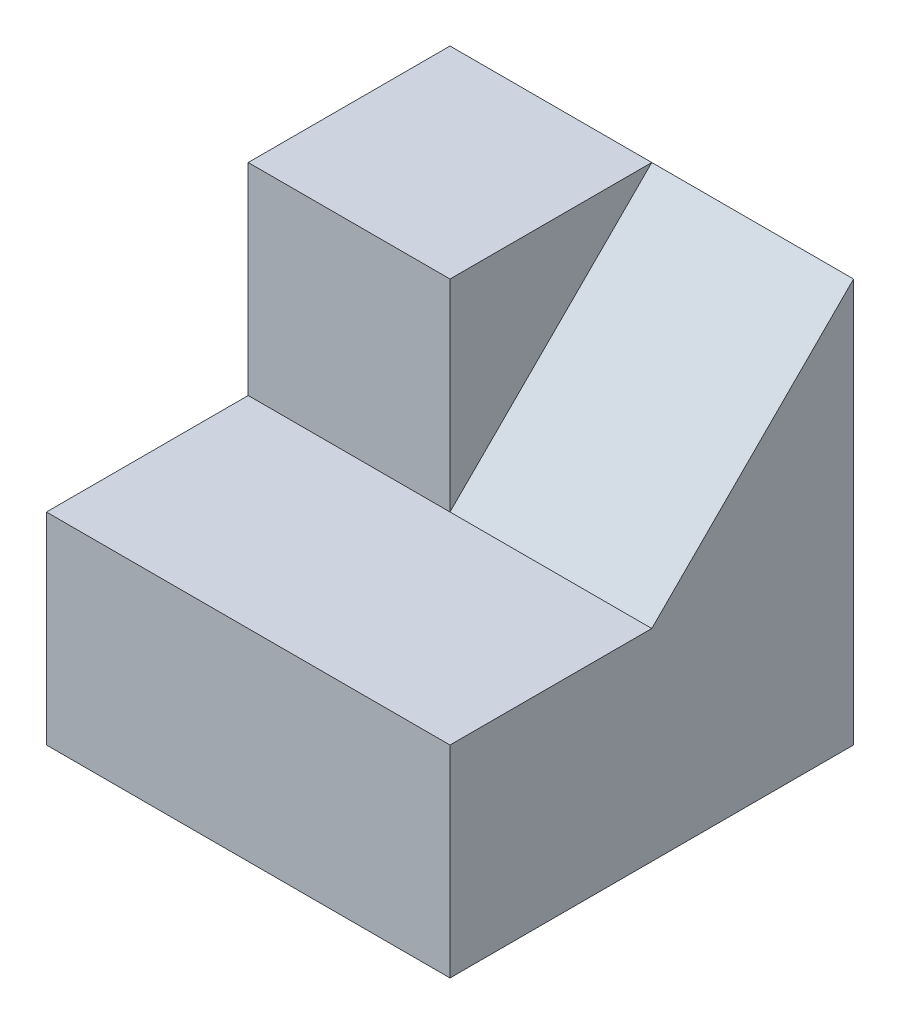
SolidWorks part; units mm, degrees
ref_plane "Alzado" through (0, 0, 0) normal (0, 0, 1) x (1, 0, 0)
ref_plane "Planta" through (0, 0, 0) normal (0, 1, 0) x (1, 0, 0)
ref_plane "Vista lateral" through (0, 0, 0) normal (1, 0, 0) x (0, 0, -1)
sketch "Croquis1" plane through (0, 0, 0) normal (0, 1, 0) x (1, 0, 0)
  line L1 (-20, 20) -> (20, 20)
  line L2 (-20, 20) -> (-20, -20)
  line L3 (-20, -20) -> (20, -20)
  line L4 (20, 20) -> (20, -20)
  line L5 (-20, 20) -> (20, -20) construction
  line L6 (-20, -20) -> (20, 20) construction
  point P0 (0, 0)
  dimension "D1" = 40
  dimension "D2" = 40
extrude "Saliente-Extruir1" add sketch "Croquis1" along normal blind 20
sketch "Croquis2" plane through (0, 20, 0) normal (0, 1, 0) x (1, 0, 0)
  line L0 (-20, 20) -> (-20, -20) construction
  line L1 (-20, 20) -> (0, 20)
  line L2 (-20, 20) -> (-20, 0)
  line L3 (-20, 0) -> (0, 0)
  line L4 (0, 20) -> (0, 0)
  line L5 (20, 20) -> (-20, 20) construction
extrude "Saliente-Extruir2" add sketch "Croquis2" along normal blind 20
sketch "Croquis3" plane through (20, 0, 0) normal (1, 0, 0) x (0, 0, -1)
  line L0 (20, 20) -> (20, 40)
  line L1 (20, 40) -> (0, 20)
  line L2 (0, 40) -> (0, 20) construction
  line L3 (0, 20) -> (20, 20) construction
  line L4 (20, 20) -> (0, 20)
extrude "Saliente-Extruir3" add sketch "Croquis3" against normal blind 20
